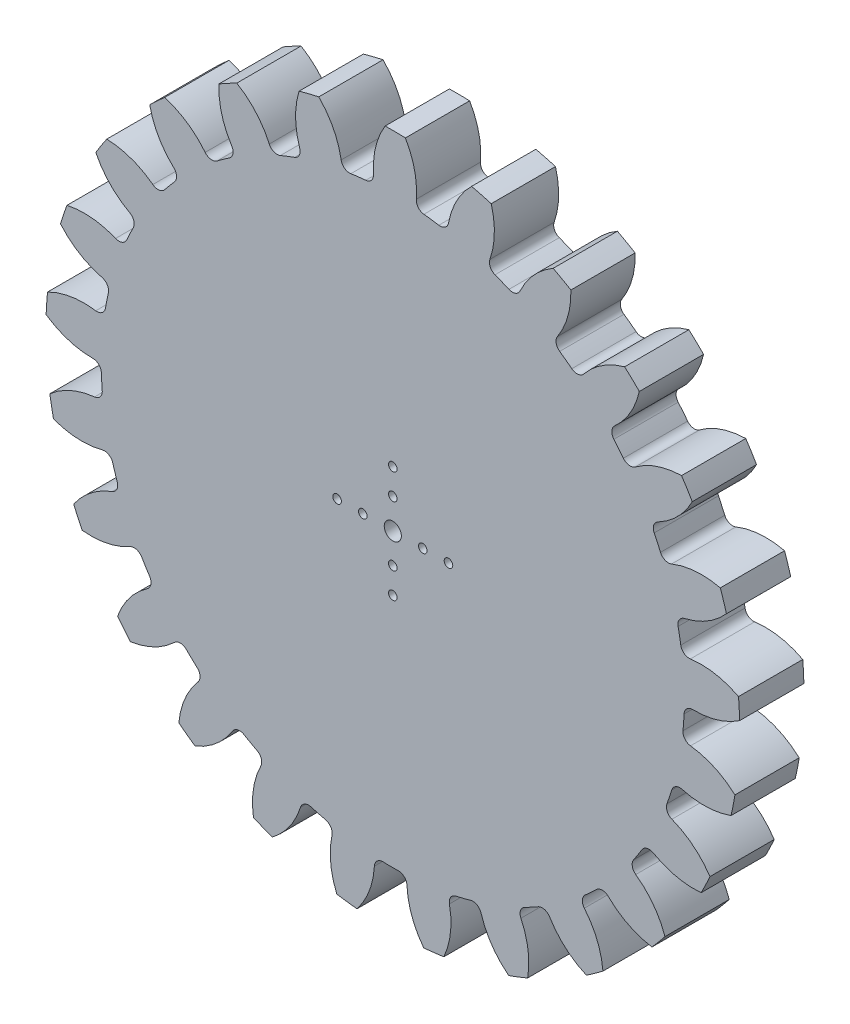
SolidWorks part; units mm, degrees
ref_plane "Front Plane" through (0, 0, 0) normal (0, 0, 1) x (1, 0, 0)
ref_plane "Top Plane" through (0, 0, 0) normal (0, 1, 0) x (1, 0, 0)
ref_plane "Right Plane" through (0, 0, 0) normal (1, 0, 0) x (0, 0, -1)
sketch "Basic Circles" plane through (0, 0, 0) normal (0, 0, 1) x (1, 0, 0)
  line L0 (0, 0) -> (0, 50000) construction
  line L2 (0, 0) -> (-50000, 0) construction
  circle A0 centre (0, 0) radius 68.058
  circle A1 centre (0, 0) radius 75
  circle A2 centre (0, 0) radius 81
sketch "Q-Circles" plane through (0, 0, 0) normal (0, 0, 1) x (1, 0, 0)
  line L0 (0, 0) -> (48.2091, 57.4533)
  line L1 (200000, 0) -> (-250000, 0) construction
  line L2 (0, -200000) -> (0, 250000) construction
  circle A0 centre (0, 0) radius 75 construction
  arc A1 (48.2091, 57.4533) -> (0, 0) centre (24.1045, 28.7267) cw construction
  arc A2 (36.1568, 43.09) -> (64.7633, 48.6489) centre (48.2091, 57.4533) ccw construction
  circle A3 centre (0, 0) radius 81 construction
  circle A4 centre (0, 0) radius 72.6184 construction
  point P3 (36.1568, 43.09)
  point P4 (48.2091, 57.4533)
  point P13 (59.1032, 42.1929)
  dimension "D3" = 18.75
  dimension "D2" = 37.5
sketch "Pressure Angle Circle" plane through (0, 0, 0) normal (0, 0, 1) x (1, 0, 0)
  line L0 (0, 0) -> (-13.0236, 73.8606)
  line L1 (0, -200000) -> (0, 250000) construction
  line L2 (34.5306, 68.9309) -> (61.8875, 45.9757) construction
  line L3 (15.042, 76.6023) -> (81.3761, 38.3043) construction
  line L4 (0, 0) -> (37.5, 64.9519)
  line L5 (0, 0) -> (48.2091, 57.4533) construction
  circle A0 centre (0, 0) radius 73.8606 construction
  circle A1 centre (0, 0) radius 75 construction
  point P10 (48.2091, 57.4533)
  point P11 (48.2091, 57.4533)
  point P16 (48.2091, 57.4533)
  point P18 (36.9303, 63.9651)
  dimension "D3" = 10
sketch "Pitch points" plane through (0, 0, 0) normal (0, 0, 1) x (1, 0, 0)
  line L0 (0, 0) -> (40.6321, 63.0399) construction
  line L1 (0, 0) -> (32.4107, 67.6354) construction
  circle A2 centre (0, 0) radius 75 construction
  circle A3 centre (0, 0) radius 75 construction
  point P1 (12.5058, 70.9056)
  point P4 (18.638, 69.5458)
  point P5 (24.6284, 67.6568)
  point P6 (30.4314, 65.2528)
  point P9 (36.0028, 62.3522)
  point P10 (40.6321, 63.0399)
  point P15 (32.4107, 67.6354)
  point P16 (23.6782, 71.1642)
  point P21 (14.5723, 73.5707)
  point P22 (5.2365, 74.817)
  point P23 (-4.1818, 74.8833)
  point P28 (-13.5342, 73.7687)
  point P29 (-22.6732, 71.4907)
  point P30 (-31.4546, 68.0853)
  point P31 (-39.7399, 63.6061)
  dimension "D2" = 7.2
  dimension "D1" = 9.42
  dimension "D3" = 10
sketch "Q-Circles (Even No Points)" plane through (0, 0, 0) normal (0, 0, 1) x (1, 0, 0)
  line L0 (0, 0) -> (-30.5449, 65.8821) construction
  line L1 (0, 0) -> (-13.2011, 71.4085) construction
  circle A0 centre (0, 0) radius 72.6184 construction
  circle A1 centre (0, 0) radius 72.6184 construction
  circle A3 centre (0, 0) radius 68.058 construction
  circle A4 centre (0, 0) radius 81 construction
  arc A5 (-49.7384, 63.9304) -> (-42.6448, 53.0407) centre (-31.4546, 68.0853) ccw
  arc A6 (-28.1144, 61.9796) -> (-32.277, 74.2913) centre (-13.5342, 73.7687) cw
  point P10 (-45.9695, 56.216)
  point P13 (-30.5449, 65.8821)
  point P15 (-13.2011, 71.4085)
  point P20 (4.9722, 72.448)
  point P23 (22.8331, 68.9354)
  point P24 (39.2593, 61.0913)
  dimension "D1" = 18.75
  dimension "D2" = 18.75
  dimension "D3" = 14.4
  dimension "D4" = 5
sketch "Q-Circles (Odd No Points)" plane through (0, 0, 0) normal (0, 0, 1) x (1, 0, 0)
  line L0 (0, 0) -> (-3.951, 72.5109) construction
  line L1 (0, 0) -> (14.2059, 71.2154) construction
  circle A0 centre (0, 0) radius 72.6184 construction
  circle A3 centre (0, 0) radius 72.6184 construction
  arc A5 (-21.0236, 64.7294) -> (-26.25, 76.6286) centre (-39.7399, 63.6061) ccw
  arc A6 (-4.2655, 67.9242) -> (-6.3685, 80.7493) centre (-22.6732, 71.4907) ccw
  circle A7 centre (0, 0) radius 68.058 construction
  circle A8 centre (0, 0) radius 81 construction
  point P14 (-3.951, 72.5109)
  point P17 (14.2059, 71.2154)
  point P21 (31.4701, 65.4452)
  point P22 (46.757, 55.5628)
  point P23 (-21.8596, 69.2503)
  point P24 (59.1059, 42.1892)
  dimension "D1" = 18.75
  dimension "D2" = 18.75
  dimension "D3" = 14.4
  dimension "D4" = 5
sketch "Gear Profile" plane through (0, 0, 0) normal (0, 0, 1) x (1, 0, 0)
  arc A1 (-28.1256, 61.9745) -> (-36.4185, 72.3512) centre (-45.9695, 56.216) ccw
  arc A5 (-36.4502, 57.4741) -> (-40.5905, 70.0957) centre (-21.8596, 69.2503) cw
  arc A6 (-11.8296, 67.022) -> (-17.2814, 79.135) centre (-30.5449, 65.8821) ccw
  arc A7 (-21.0118, 64.7333) -> (-21.8832, 77.988) centre (-3.951, 72.5109) cw
  circle A8 centre (0, 0) radius 68.058 construction
  circle A9 centre (0, 0) radius 81 construction
sketch "Sketch12" plane through (0, 0, 0) normal (0, 0, 1) x (1, 0, 0)
  circle A0 centre (0, 0) radius 68.058 construction
  circle A1 centre (0, 0) radius 68.058
extrude "Boss-Extrude2" add sketch "Sketch12" along normal mid plane 15
sketch "Sketch13" plane through (0, 0, 0) normal (0, 0, 1) x (1, 0, 0)
  circle A4 centre (0, 0) radius 68.058 construction
  circle A5 centre (0, 0) radius 81 construction
  arc A6 (-28.1256, 61.9745) -> (-36.4185, 72.3512) centre (-45.9695, 56.216) ccw construction
  arc A7 (-40.5905, 70.0957) -> (-36.4502, 57.4741) centre (-21.8596, 69.2503) ccw construction
  arc A8 (-28.1256, 61.9745) -> (-36.4502, 57.4741) centre (0, 0) ccw
  arc A9 (-36.4185, 72.3512) -> (-40.5905, 70.0957) centre (0, 0) ccw
  arc A10 (-28.1256, 61.9745) -> (-36.4185, 72.3512) centre (-45.9695, 56.216) ccw
  arc A11 (-40.5905, 70.0957) -> (-36.4502, 57.4741) centre (-21.8596, 69.2503) ccw
extrude "Boss-Extrude3" add sketch "Sketch13" along normal mid plane 15
fillet "Fillet1" radius 2 2 edges at (-36.4502, 57.4741, 0) (-28.1256, 61.9745, 0)
pattern_circular "CirPattern2" count 25 over 360 about axis through (0, 0, 0) along (0, 0, 1) of "Boss-Extrude3", "Fillet1"
sketch "Croquis1" plane through (0, 0, -7.5) normal (0, 0, -1) x (-1, 0, 0)
  line L0 (0, 0) -> (7, 0) construction
  line L1 (0, 0) -> (-7, 0) construction
  line L2 (7, 0) -> (13, 0) construction
  line L3 (-7, 0) -> (-13, 0) construction
  circle A0 centre (0, 0) radius 18 construction
  circle A1 centre (7, 0) radius 1
  circle A2 centre (13, 0) radius 1
  circle A3 centre (-7, 0) radius 1
  circle A4 centre (-13, 0) radius 1
  dimension "D1" = 36
  dimension "D3" = 2
  dimension "D5" = 2
  dimension "D8" = 2
  dimension "D9" = 2
  dimension "D2" = 7
  dimension "D4" = 6
  dimension "D6" = 7
  dimension "D7" = 6
extrude "Cortar-Extruir1" cut sketch "Croquis1" against normal blind 15
sketch "Croquis2" plane through (0, 0, -7.5) normal (0, 0, -1) x (-1, 0, 0)
  circle A0 centre (0, 0) radius 2
  dimension "D1" = 4
extrude "Cortar-Extruir2" cut sketch "Croquis2" against normal blind 15
sketch "Sketch14" plane through (0, 0, -7.5) normal (0, 0, -1) x (-1, 0, 0)
  line L0 (0, 0) -> (0, 7) construction
  line L1 (0, 7) -> (0, 13) construction
  line L2 (0, 0) -> (0, -7) construction
  line L3 (0, -7) -> (0, -13) construction
  circle A0 centre (0, 7) radius 1
  circle A1 centre (0, 13) radius 1
  circle A2 centre (0, -7) radius 1
  circle A3 centre (0, -13) radius 1
  dimension "D2" = 2
  dimension "D4" = 2
  dimension "D7" = 2
  dimension "D8" = 2
  dimension "D1" = 7
  dimension "D3" = 6
  dimension "D5" = 7
  dimension "D6" = 6
extrude "Cut-Extrude1" cut sketch "Sketch14" against normal blind 15
equation "\"module\"= 6"
equation "\"no of teeth\"= 25"
equation "\"addendum\"= \"module\" * 1"
equation "\"clearence\"= \"module\" * .157"
equation "\"dedendum\"= \"addendum\" + \"clearence\""
equation "\"circular pitch\"= \"module\" * 3.14"
equation "\"D1@Basic Circles\" = \"module\" * \"no of teeth\""
equation "\"D2@Basic Circles\"= \"D1@Basic Circles\" + 2 * \"addendum\""
equation "\"D3@Basic Circles\" = \"D1@Basic Circles\" - 2 * \"dedendum\""
equation "\"D3@Q-Circles\"= \"module\" * \"no of teeth\" / 8"
equation "\"D1@Boss-Extrude2\"=\"module\"*2.5"
equation "\"D1@Boss-Extrude3\"=\"module\"*2.5"
equation "\"D1@Pitch points\"   = \"circular pitch\" / 2"
equation "\"D2@Pitch points\"   = ( \"D1@Pitch points\" * 360 ) / ( 3.14 * \"module\" * \"no of teeth\" )"
equation "\"D1@Q-Circles (Even No Points)\"= \"module\" * \"no of teeth\" / 8"
equation "\"D2@Q-Circles (Even No Points)\" = \"module\" * \"no of teeth\" / 8"
equation "\"D3@Q-Circles (Even No Points)\" = ( \"circular pitch\" / 2 * 360 ) / ( \"module\" * \"no of teeth\" * 3.14 ) * 2"
equation "\"D1@Q-Circles (Odd No Points)\"   = \"module\" * \"no of teeth\" / 8"
equation "\"D2@Q-Circles (Odd No Points)\"   = \"module\" * \"no of teeth\" / 8"
equation "\"D3@Q-Circles (Odd No Points)\" = ( \"circular pitch\" / 2 * 360 ) / ( \"module\" * \"no of teeth\" * 3.14 ) * 2"
equation "\"D1@CirPattern2\" = \"no of teeth\""
equation "\"Pressure Angle\"= 10deg"
equation "\"D2@Pressure Angle Circle\" = \"Pressure Angle\""
equation "\"D3@Pressure Angle Circle\" = \"Pressure Angle\""
equation "\"D1@Pressure Angle Circle\" = \"Pressure Angle\""
